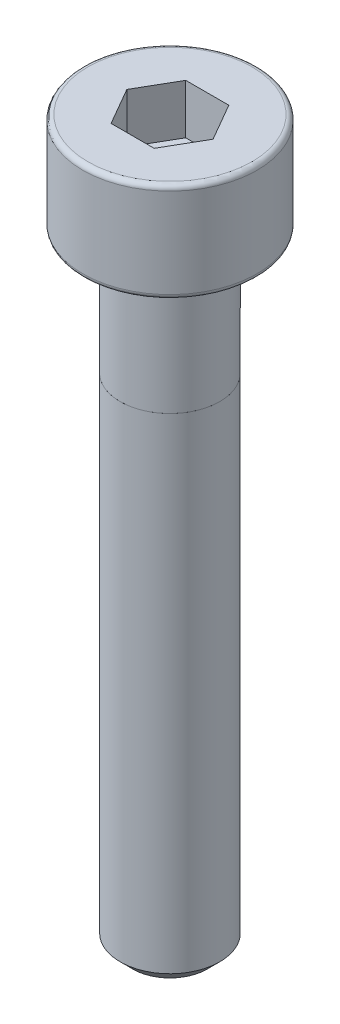
SolidWorks part; units mm, degrees
ref_plane "Front Plane" through (0, 0, 0) normal (0, 0, 1) x (1, 0, 0)
ref_plane "Top Plane" through (0, 0, 0) normal (0, 1, 0) x (1, 0, 0)
ref_plane "Right Plane" through (0, 0, 0) normal (1, 0, 0) x (0, 0, -1)
sketch "Sketch1" plane through (0, 0, 0) normal (0, 1, 0) x (1, 0, 0)
  circle A0 centre (0, 0) radius 3.5
  dimension "D1" = 7
extrude "Boss-Extrude1" add sketch "Sketch1" against normal blind 4
sketch "Sketch2" plane through (0, 0, 0) normal (0, 1, 0) x (1, 0, 0)
  line L1 (1.7321, 0) -> (0.866, 1.5)
  line L2 (0.866, 1.5) -> (-0.866, 1.5)
  line L3 (-0.866, 1.5) -> (-1.7321, 0)
  line L4 (-1.7321, 0) -> (-0.866, -1.5)
  line L5 (-0.866, -1.5) -> (0.866, -1.5)
  line L6 (0.866, -1.5) -> (1.7321, 0)
  circle A0 centre (0, 0) radius 1.5 construction
  dimension "D1" = 3
extrude "Cut-Extrude1" cut sketch "Sketch2" against normal blind 2
sketch "Sketch3" plane through (0, -4, 0) normal (0, -1, 0) x (1, 0, 0)
  circle A0 centre (0, 0) radius 2
  dimension "D1" = 4
extrude "Boss-Extrude2" add sketch "Sketch3" along normal blind 5
sketch "Sketch4" plane through (0, -9, 0) normal (0, -1, 0) x (1, 0, 0)
  circle A0 centre (0, 0) radius 2
  circle A1 centre (0, 0) radius 2 construction
extrude "Boss-Extrude3" add sketch "Sketch4" along normal blind 20 separate body
chamfer "Chamfer1" distance 0.5 angle 45 1 edges at (0, -29, -2)
fillet "Fillet1" radius 0.2 2 edges at (0, -4, 3.5) (0, 0, 3.5)
